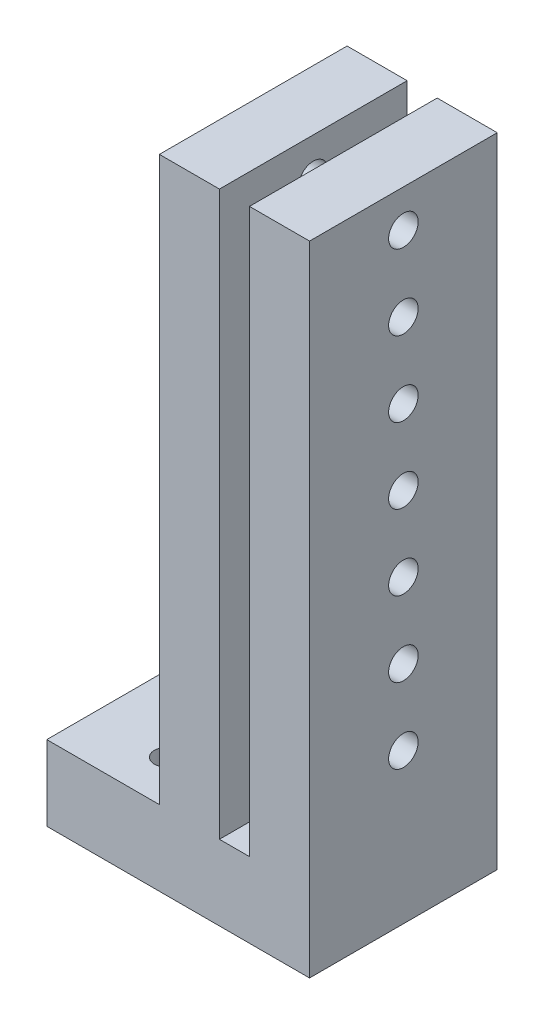
SolidWorks part; units mm, degrees
material "PBT General Purpose"
ref_plane "Front Plane" through (0, 0, 0) normal (0, 0, 1) x (1, 0, 0)
ref_plane "Top Plane" through (0, 0, 0) normal (0, 1, 0) x (1, 0, 0)
ref_plane "Right Plane" through (0, 0, 0) normal (1, 0, 0) x (0, 0, -1)
sketch "Sketch1" plane through (0, 0, 0) normal (0, 1, 0) x (1, 0, 0)
  line L1 (0, 0) -> (50, 0)
  line L2 (0, 0) -> (0, 25)
  line L3 (0, 25) -> (50, 25)
  line L4 (50, 0) -> (50, 25)
  dimension "D1" = 50
  dimension "D2" = 25
extrude "Boss-Extrude1" add sketch "Sketch1" along normal blind 10
sketch "Sketch2" plane through (0, 10, 0) normal (0, 1, 0) x (1, 0, 0)
  line L0 (50, 25) -> (0, 25) construction
  line L1 (15, 25) -> (35, 25)
  line L2 (15, 25) -> (15, 0)
  line L3 (15, 0) -> (35, 0)
  line L4 (35, 25) -> (35, 0)
  line L5 (0, 0) -> (50, 0) construction
  point P8 (25, 25)
  point P9 (25, 25)
  dimension "D1" = 20
extrude "Boss-Extrude2" add sketch "Sketch2" along normal blind 75
sketch "Sketch3" plane through (0, 85, 0) normal (0, 1, 0) x (1, 0, 0)
  line L0 (35, 25) -> (15, 25) construction
  line L1 (23, 25) -> (27, 25)
  line L2 (23, 25) -> (23, 0)
  line L3 (23, 0) -> (27, 0)
  line L4 (27, 25) -> (27, 0)
  line L5 (15, 0) -> (35, 0) construction
  point P8 (25, 25)
  point P9 (25, 25)
  dimension "D1" = 4
extrude "Cut-Extrude1" cut sketch "Sketch3" against normal up to surface (75 mm away) up to face at (7.5, 10, -12.5)
sketch "Sketch4" plane through (15, 0, 0) normal (-1, 0, 0) x (0, 0, 1)
  line L0 (-12.5, 85) -> (-12.5, 80) construction
  line L1 (-25, 85) -> (0, 85) construction
  circle A0 centre (-12.5, 80) radius 1.967
  dimension "D1" = 5
extrude "Cut-Extrude2" cut sketch "Sketch4" against normal through all
pattern_linear "LPattern1" count 7 spacing 10 along (0, -1, 0) of "Cut-Extrude2"
sketch "Sketch5" plane through (0, 10, 0) normal (0, 1, 0) x (1, 0, 0)
  line L4 (35, 25) -> (35, 0)
  line L5 (35, 0) -> (50, 0)
  line L6 (50, 0) -> (50, 25)
  line L7 (50, 25) -> (35, 25)
  line L8 (35, 25) -> (35, 0)
  line L9 (35, 0) -> (50, 0)
  line L10 (50, 0) -> (50, 25)
  line L11 (50, 25) -> (35, 25)
  dimension "D1" = 0
extrude "Cut-Extrude3" cut sketch "Sketch5" against normal through all
ref_plane "Plane1" through (25, 0, 0) normal (1, 0, 0) x (0, 0, -1)
sketch "Sketch6" plane through (0, 0, 0) normal (0, -1, 0) x (1, 0, 0)
  circle A0 centre (10.0004, -19.0694) radius 1.6 construction
  circle A1 centre (10.0004, -19.0694) radius 1.6
extrude "Cut-Extrude4" cut sketch "Sketch6" against normal through all
ref_plane "Plane2" through (0, 0, -12.5) normal (0, 0, 1) x (1, 0, 0)
mirror "Mirror1" about plane through (0, 0, -12.5) normal (0, 0, 1) of "Cut-Extrude4"
